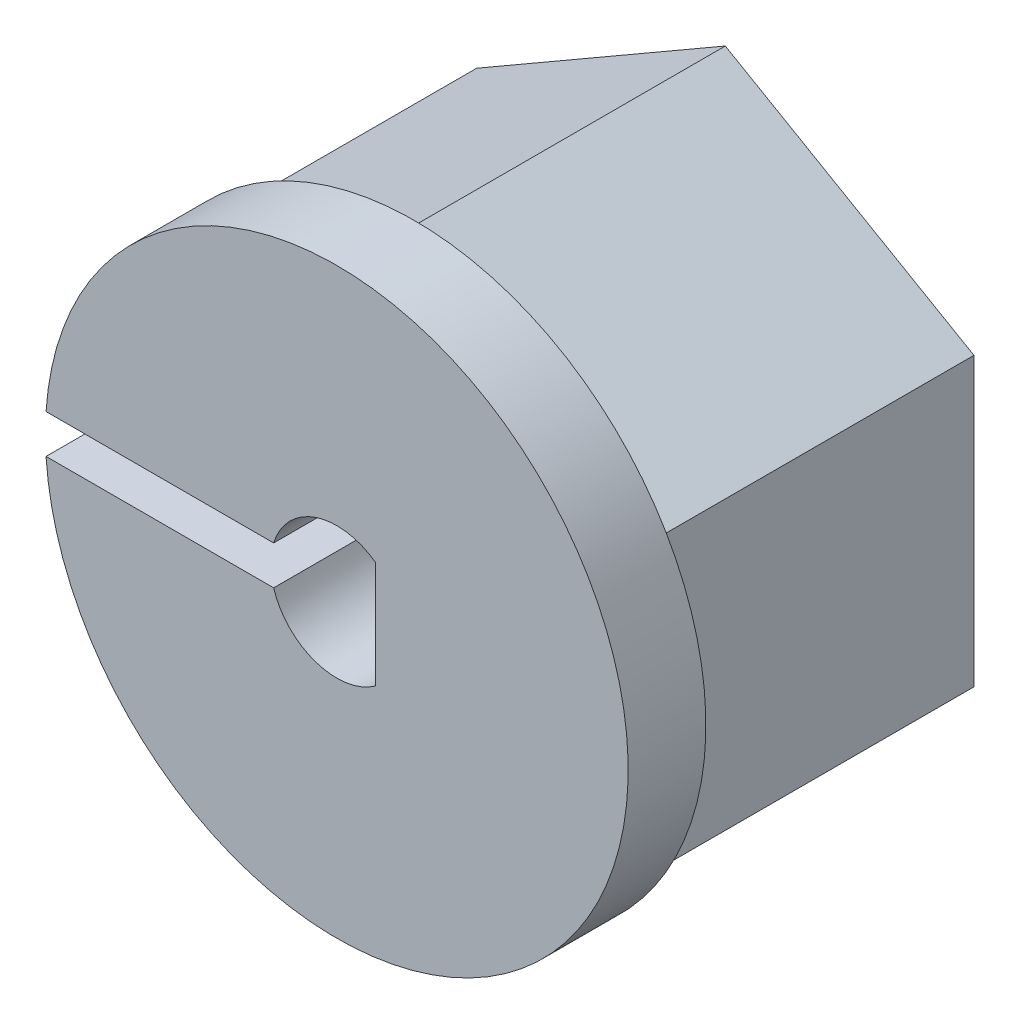
SolidWorks part; units mm, degrees
ref_plane "Plan de face" through (0, 0, 0) normal (0, 0, 1) x (1, 0, 0)
ref_plane "Plan de dessus" through (0, 0, 0) normal (0, 1, 0) x (1, 0, 0)
ref_plane "Plan de droite" through (0, 0, 0) normal (1, 0, 0) x (0, 0, -1)
sketch "Esquisse1" plane through (0, 0, 0) normal (0, 0, 1) x (1, 0, 0)
  line L1 (0, 7.3901) -> (-6.4, 3.695)
  line L2 (-6.4, 3.695) -> (-6.4, -3.695)
  line L3 (-6.4, -3.695) -> (0, -7.3901)
  line L4 (0, -7.3901) -> (6.4, -3.695)
  line L5 (6.4, -3.695) -> (6.4, 3.695)
  line L6 (6.4, 3.695) -> (0, 7.3901)
  circle A0 centre (0, 0) radius 6.4 construction
  dimension "D1" = 12.8
extrude "Boss.-Extru.1" add sketch "Esquisse1" along normal blind 8
sketch "Esquisse2" plane through (0, 0, 8) normal (0, 0, 1) x (1, 0, 0)
  circle A0 centre (0, 0) radius 7.5
  dimension "D1" = 15
extrude "Boss.-Extru.2" add sketch "Esquisse2" along normal blind 2
sketch "Esquisse3" plane through (0, 0, 0) normal (0, 0, -1) x (-1, 0, 0)
  line L0 (-1, 1.3748) -> (-1, -1.3748)
  line L1 (1.4142, 0) -> (8.491, 0) construction
  line L3 (1.6248, 0.5) -> (8.491, 0.5)
  line L5 (1.6248, -0.5) -> (8.491, -0.5)
  line L6 (8.491, 0.5) -> (8.491, -0.5)
  arc A0 (-1, -1.3748) -> (1.6248, -0.5) centre (0, 0) ccw
  arc A1 (1.6248, 0.5) -> (-1, 1.3748) centre (0, 0) ccw
  dimension "D2" = 1.7
  dimension "D1" = 1
  dimension "D3" = 1
extrude "Enlèv. mat.-Extru.1" cut sketch "Esquisse3" against normal up to next
